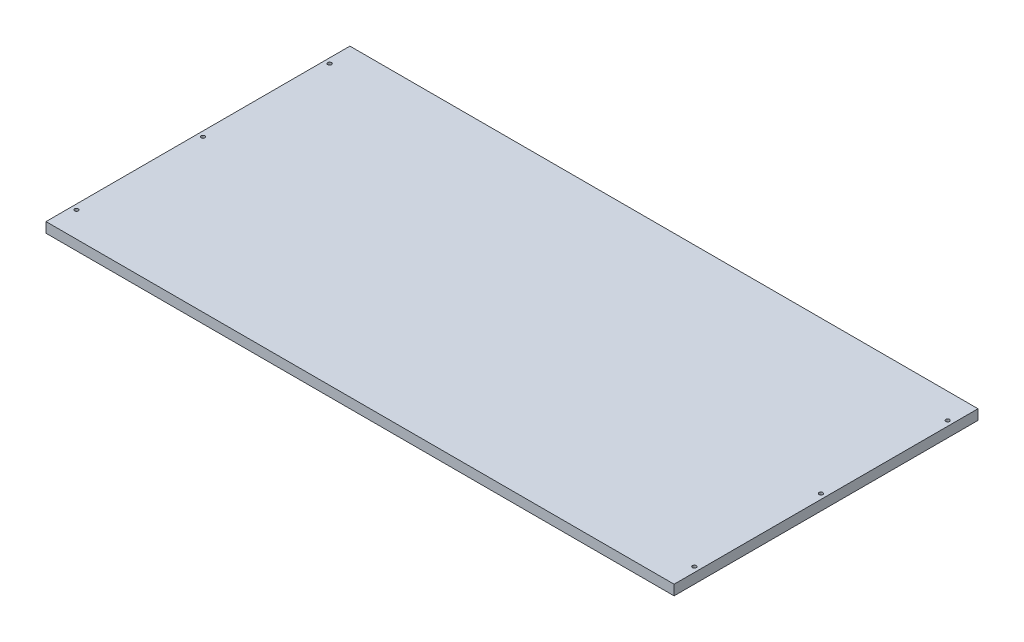
SolidWorks part; units mm, degrees
material "Дуб"
ref_plane "Front Plane" through (0, 0, 0) normal (0, 0, 1) x (1, 0, 0)
ref_plane "Top Plane" through (0, 0, 0) normal (0, 1, 0) x (1, 0, 0)
ref_plane "Right Plane" through (0, 0, 0) normal (1, 0, 0) x (0, 0, -1)
sketch "Эскиз1" plane through (0, 0, 0) normal (0, 1, 0) x (1, 0, 0)
  line L1 (-372, 180) -> (0, 180)
  line L2 (-372, 180) -> (-372, 0)
  line L3 (-372, 0) -> (0, 0)
  line L4 (0, 180) -> (0, 0)
  circle A0 centre (-369, 165) radius 1.1
  circle A1 centre (-369, 15) radius 1.1
  circle A2 centre (-3, 165) radius 1.1
  circle A3 centre (-3, 15) radius 1.1
  circle A4 centre (-369, 90) radius 1.1
  circle A5 centre (-3, 90) radius 1.1
  point P17 (-372, 90)
  dimension "D3" = 2.2
  dimension "D5" = 3
  dimension "D6" = 15
  dimension "D7" = 15
  dimension "D1" = 180
  dimension "D2" = 372
  dimension "D4" = 3
extrude "Бобышка-Вытянуть1" add sketch "Эскиз1" along normal blind 6
